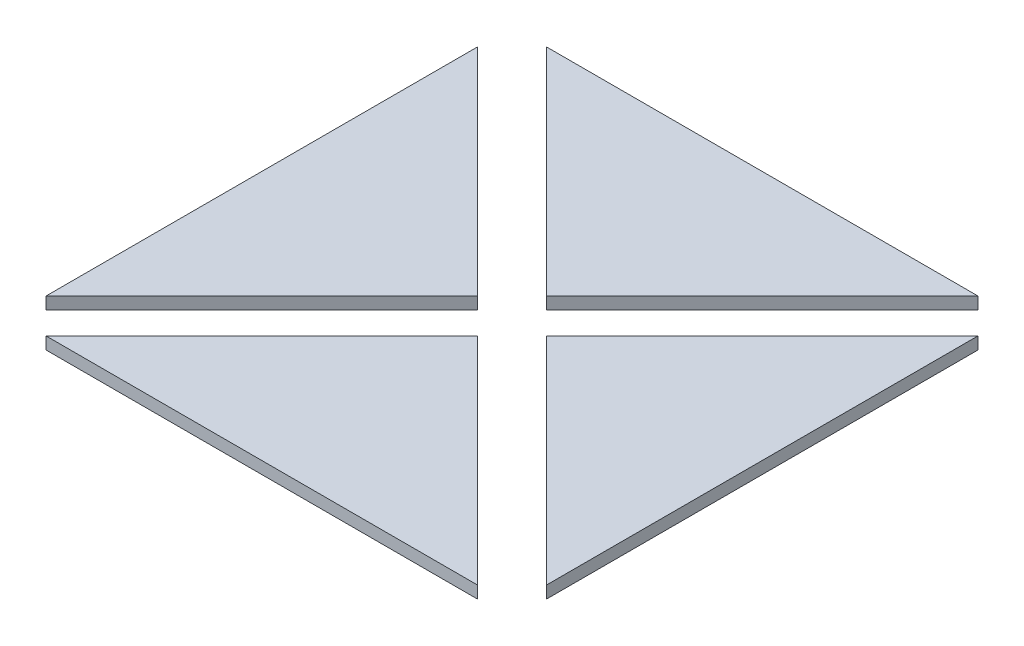
SolidWorks part; units mm, degrees
ref_plane "Front Plane" through (0, 0, 0) normal (0, 0, 1) x (1, 0, 0)
ref_plane "Top Plane" through (0, 0, 0) normal (0, 1, 0) x (1, 0, 0)
ref_plane "Right Plane" through (0, 0, 0) normal (1, 0, 0) x (0, 0, -1)
sketch "Sketch1" plane through (0, 0, 0) normal (0, 1, 0) x (1, 0, 0)
  line L0 (-205, -176.7157) -> (176.7157, 205)
  line L1 (-205, -205) -> (205, -205)
  line L2 (-205, -205) -> (-205, 205)
  line L3 (-205, 205) -> (205, 205)
  line L4 (205, -205) -> (205, 205)
  line L5 (-205, -205) -> (205, 205) construction
  line L6 (-205, 205) -> (205, -205) construction
  line L7 (-176.7157, -205) -> (205, 176.7157)
  line L8 (-176.7157, 205) -> (205, -176.7157)
  line L9 (-205, 176.7157) -> (176.7157, -205)
  point P0 (0, 0)
  dimension "D1" = 410
  dimension "D2" = 410
  dimension "D3" = 20
  dimension "D4" = 20
  dimension "D5" = 20
  dimension "D6" = 20
extrude "Boss-Extrude1" add sketch "Sketch1" along normal blind 10 contours L9 L2 L0 | L3 L8 L0 | L7 L8 L4 | L9 L7 L1
